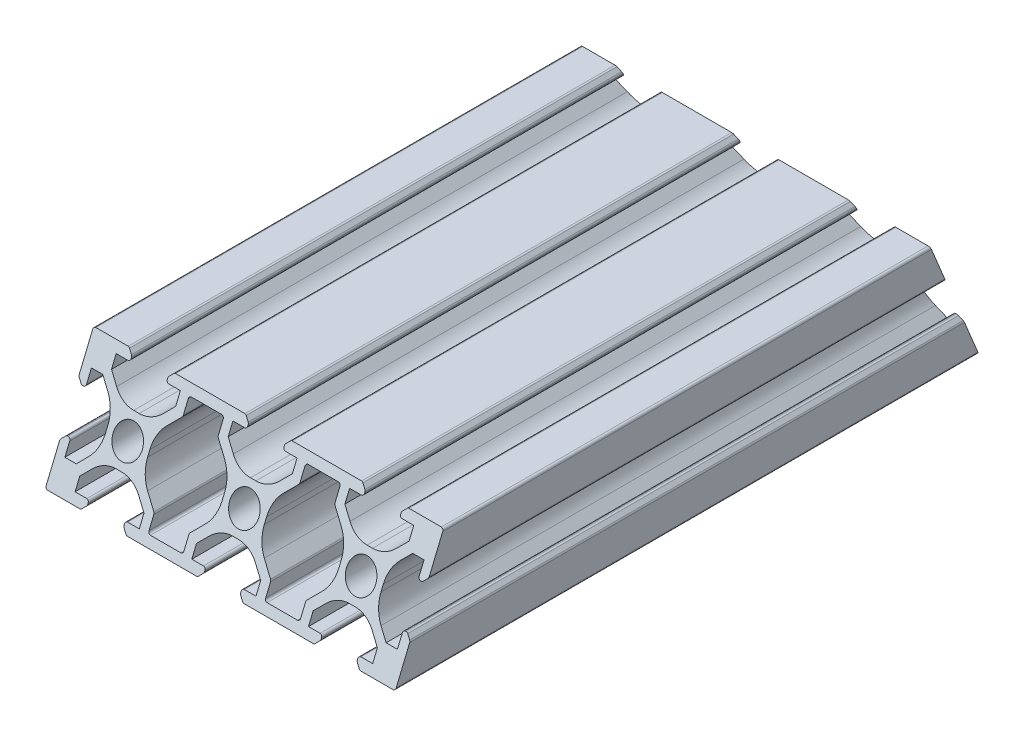
SolidWorks part; units mm, degrees
material "6063-T83"
ref_plane "Plano frontal" through (0, 0, 0) normal (0, 0, 1) x (1, 0, 0)
ref_plane "Plano superior" through (0, 0, 0) normal (0, 1, 0) x (1, 0, 0)
ref_plane "Plano direito" through (0, 0, 0) normal (1, 0, 0) x (0, 0, -1)
sketch "Esboço1" plane through (0, 0, 0) normal (0, 0, 1) x (1, 0, 0)
  line L0 (-9.0343, 3.1) -> (-8.9, 3.1)
  line L3 (-10, 10) -> (-4.0657, 10)
  line L5 (-10, -10) -> (10, 10) construction
  line L6 (-10, 10) -> (10, -10) construction
  line L7 (-8.5, 3.5) -> (-8.5, 5.5)
  line L8 (-10, 0) -> (10, 0) construction
  line L9 (0, 10) -> (0, -10) construction
  line L12 (-8.5, 5.5) -> (-6.5607, 5.5)
  line L15 (-6.5607, 5.5) -> (-5.0645, 4.0038)
  line L16 (-3.6, 0.4683) -> (-3.6, 0)
  line L17 (-0.4683, 3.6) -> (0, 3.6)
  line L18 (-5.5, 6.5607) -> (-4.0038, 5.0645)
  line L21 (-5.5, 8.5) -> (-5.5, 6.5607)
  line L24 (-3.5, 8.5) -> (-5.5, 8.5)
  line L25 (-3.1, 9.0343) -> (-3.1, 8.9)
  line L44 (-10, 4.0657) -> (-10, 10)
  line L45 (-9.8828, 3.7828) -> (-9.3172, 3.2172)
  line L46 (-3.7828, 9.8828) -> (-3.2172, 9.3172)
  line L47 (-3.6, 0) -> (-2.5, 0)
  line L48 (0, 3.6) -> (0, 2.5)
  arc A0 (-3.5, 8.5) -> (-3.1, 8.9) centre (-3.5, 8.9) ccw
  arc A1 (-3.7828, 9.8828) -> (-4.0657, 10) centre (-4.0657, 9.6) ccw
  arc A2 (-10, 4.0657) -> (-9.8828, 3.7828) centre (-9.6, 4.0657) ccw
  arc A3 (-8.5, 3.5) -> (-8.9, 3.1) centre (-8.9, 3.5) cw
  arc A4 (-3.2172, 9.3172) -> (-3.1, 9.0343) centre (-3.5, 9.0343) cw
  arc A5 (-9.3172, 3.2172) -> (-9.0343, 3.1) centre (-9.0343, 3.5) ccw
  arc A6 (-3.6, 0.4683) -> (-5.0645, 4.0038) centre (-8.6, 0.4683) ccw
  arc A7 (-4.0038, 5.0645) -> (-0.4683, 3.6) centre (-0.4683, 8.6) ccw
  circle A8 centre (0, 0) radius 2.5
  point P6 (-10, 3.1)
  point P28 (-3.1, 8.5)
  point P31 (-3.1, 10)
  point P33 (-3.9, 10)
  point P36 (-10, 3.9)
  point P39 (-8.5, 3.1)
  point P42 (-3.1, 9.2)
  point P45 (-9.2, 3.1)
  point P48 (-3.6, 2.5393)
  point P51 (-2.5393, 3.6)
  dimension "D5" = 10
  dimension "D9" = 0.4
  dimension "D10" = 0.4
  dimension "D11" = 5
  dimension "D12" = 5
  dimension "D13" = 5
  dimension "D1" = 6.9
  dimension "D2" = 1.5
  dimension "D3" = 3.6
  dimension "D4" = 1.5
  dimension "D6" = 2.4
  dimension "D7" = 3.6
  dimension "D8" = 45
extrude "Ressalto-extrusão1" add sketch "Esboço1" along normal blind 100
sketch "Esboço3" plane through (0, 0, 0) normal (1, 0, 0) x (0, 0, -1)
  line L0 (0, 0) -> (-100, 0) construction
pattern_circular "PadrãoCircular1" count 4 over 360 about axis through (0, 0, 0) along (0, 0, 1) of "Ressalto-extrusão1"
pattern_linear "Padrão linear1" count 3 spacing 20 along (1, 0, 0) of "Ressalto-extrusão1", "PadrãoCircular1"
sketch "Esboço4" plane through (0, 0, 0) normal (0, 0, -1) x (-1, 0, 0)
  line L0 (-13.4393, 5.5) -> (-13, 5.9393)
  line L1 (-13, 8.5) -> (-13, 5.9393)
  line L2 (-10, 10) -> (-10, -10) construction
  line L3 (-4.0657, 10) -> (-15.9343, 10) construction
  line L4 (-15.9343, -10) -> (-4.0657, -10) construction
  line L5 (-11.5, 5.5) -> (-13.4393, 5.5) construction
  line L6 (-14.5, 8.5) -> (-14.5, 6.5607) construction
  line L7 (-7, 8.5) -> (-7, 5.9393)
  line L8 (-6.5607, 5.5) -> (-7, 5.9393)
  line L9 (-13, 8.5) -> (-7, 8.5)
  line L10 (-20, 0) -> (0, 0) construction
  line L11 (-13, -8.5) -> (-7, -8.5)
  line L12 (-6.5607, -5.5) -> (-7, -5.9393)
  line L13 (-7, -8.5) -> (-7, -5.9393)
  line L14 (-13, -8.5) -> (-13, -5.9393)
  line L15 (-13.4393, -5.5) -> (-13, -5.9393)
  line L16 (-13.4393, 5.5) -> (-13.4393, -5.5)
  line L17 (-6.5607, -5.5) -> (-6.5607, 5.5)
  line L31 (-40, 0) -> (-20, 0) construction
  line L32 (-33.4393, 5.5) -> (-33, 5.9393) [skipped]
  line L33 (-33, 8.5) -> (-33, 5.9393) [skipped]
  line L34 (-27, 8.5) -> (-27, 5.9393) [skipped]
  line L35 (-26.5607, 5.5) -> (-27, 5.9393) [skipped]
  line L36 (-33, 8.5) -> (-27, 8.5) [skipped]
  line L37 (-33, -8.5) -> (-27, -8.5) [skipped]
  line L38 (-26.5607, -5.5) -> (-27, -5.9393) [skipped]
  line L39 (-27, -8.5) -> (-27, -5.9393) [skipped]
  line L40 (-33, -8.5) -> (-33, -5.9393) [skipped]
  line L41 (-33.4393, -5.5) -> (-33, -5.9393) [skipped]
  line L42 (-33.4393, 5.5) -> (-33.4393, -5.5) [skipped]
  line L43 (-26.5607, -5.5) -> (-26.5607, 5.5) [skipped]
  line L44 (-30, 10) -> (-30, -10) construction
  dimension "D1" = 45
  dimension "D2" = 1.5
  dimension "D3" = 1.5
  dimension "D4" = 2
extrude "Corte-extrusão1" cut sketch "Esboço4" against normal through all
pattern_linear "Padrão linear2" count 2 spacing 20 along (1, 0, 0) of "Corte-extrusão1"
fillet "Filete1" radius 0.4 16 edges at (13, -5.9393, 50) (13, -8.5, 50) (7, -8.5, 50) (7, -5.9393, 50) (7, 8.5, 50) (7, 5.9393, 50) (13, 8.5, 50) (13, 5.9393, 50) (27, -8.5, 50) (27, -5.9393, 50) (27, 8.5, 50) (27, 5.9393, 50) (33, 8.5, 50) (33, -8.5, 50) (33, -5.9393, 50) (33, 5.9393, 50)
fillet "Filete2" radius 0.4 4 edges at (-10, 10, 50) (50, -10, 50) (50, 10, 50) (-10, -10, 50)
sketch "Sketch1" plane through (-10, 0, 0) normal (-1, 0, 0) x (0, 0, 1)
  line L4 (100, 9.6) -> (0, 9.6) construction
  line L6 (50, 9.6) -> (50, -9.6) construction
  line L7 (0, -9.6) -> (100, -9.6) construction
  line L11 (0, 0) -> (0, -10)
  line L12 (0, -10) -> (12.4264, 20)
  line L13 (12.4264, 20) -> (0, 20)
  line L14 (0, 20) -> (0, 0)
  line L15 (87.5736, 20) -> (100, 20)
  line L16 (100, -10) -> (87.5736, 20)
  line L17 (100, 0) -> (100, -10)
  line L18 (100, 20) -> (100, 0)
  dimension "D1" = 10
  dimension "D2" = 20
  dimension "D3" = 22.5
extrude "Cut-Extrude1" cut sketch "Sketch1" against normal through all
sketch "Sketch2" plane through (0, -10, 0) normal (0, -1, 0) x (1, 0, 0)
  line L0 (-9.6, 50) -> (49.6, 50)
  line L1 (-9.6, 100) -> (-9.6, 0) construction
  line L2 (49.6, 0) -> (49.6, 100) construction
